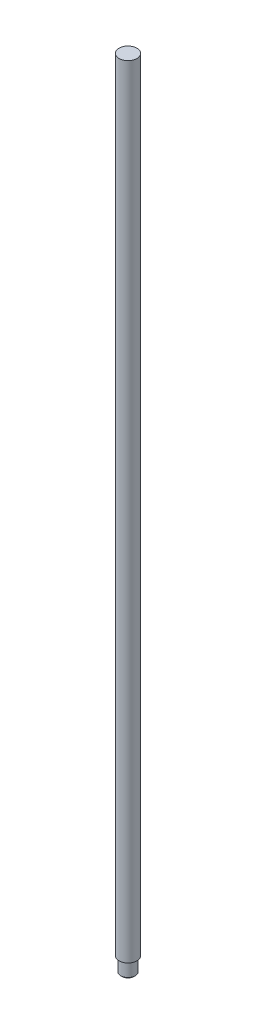
SolidWorks part; units mm, degrees
material "Plain Carbon Steel"
ref_plane "Front Plane" through (0, 0, 0) normal (0, 0, 1) x (1, 0, 0)
ref_plane "Top Plane" through (0, 0, 0) normal (0, 1, 0) x (1, 0, 0)
ref_plane "Right Plane" through (0, 0, 0) normal (1, 0, 0) x (0, 0, -1)
sketch "Sketch1" plane through (0, 0, 0) normal (0, 1, 0) x (1, 0, 0)
  circle A0 centre (0, 0) radius 4.953
  dimension "D1" = 9.906
extrude "Boss-Extrude1" add sketch "Sketch1" along normal blind 431.8
sketch "Sketch2" plane through (0, 0, 0) normal (0, -1, 0) x (1, 0, 0)
  circle A0 centre (0, 0) radius 4
  dimension "D1" = 8
extrude "Boss-Extrude2" add sketch "Sketch2" along normal blind 8.382
chamfer "Chamfer1" distance 0.762 angle 45 1 edges at (0, -8.382, -4)
